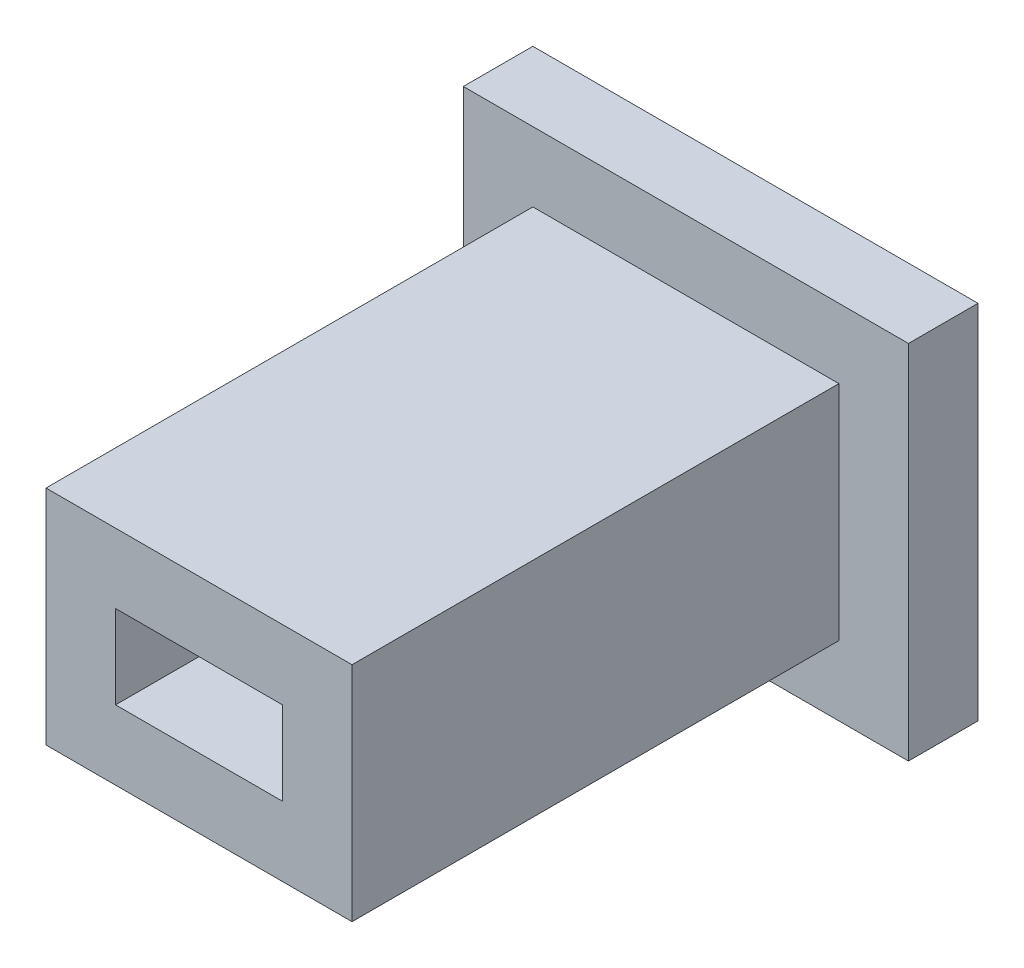
SolidWorks part; units mm, degrees
ref_plane "前视基准面" through (0, 0, 0) normal (0, 0, 1) x (1, 0, 0)
ref_plane "上视基准面" through (0, 0, 0) normal (0, 1, 0) x (1, 0, 0)
ref_plane "右视基准面" through (0, 0, 0) normal (1, 0, 0) x (0, 0, -1)
other "Configuration Table"
sketch "草图1" plane through (0, 0, 0) normal (0, 0, 1) x (1, 0, 0)
  line L1 (-12, -6) -> (12, -6)
  line L2 (-12, -6) -> (-12, 6)
  line L3 (-12, 6) -> (12, 6)
  line L4 (12, -6) -> (12, 6)
  line L7 (-22, -16) -> (22, -16)
  line L8 (-22, -16) -> (-22, 16)
  line L9 (-22, 16) -> (22, 16)
  line L10 (22, -16) -> (22, 16)
  point P0 (0, 0)
  point P6 (0, 0)
  dimension "D1" = 24
  dimension "D2" = 12
  dimension "D3" = 44
  dimension "D4" = 32
extrude "凸台-拉伸1" add sketch "草图1" along normal blind 80
sketch "草图2" plane through (0, 0, 0) normal (0, 0, -1) x (-1, 0, 0)
  line L1 (-22, -16) -> (22, -16)
  line L2 (-22, -16) -> (-22, 16)
  line L3 (-22, 16) -> (22, 16)
  line L4 (22, -16) -> (22, 16)
  line L7 (-32, -26) -> (32, -26)
  line L8 (-32, -26) -> (-32, 26)
  line L9 (-32, 26) -> (32, 26)
  line L10 (32, -26) -> (32, 26)
  point P0 (0, 0)
  point P7 (0, 0)
  dimension "D1" = 10
  dimension "D2" = 10
extrude "凸台-拉伸2" add sketch "草图2" against normal blind 10
